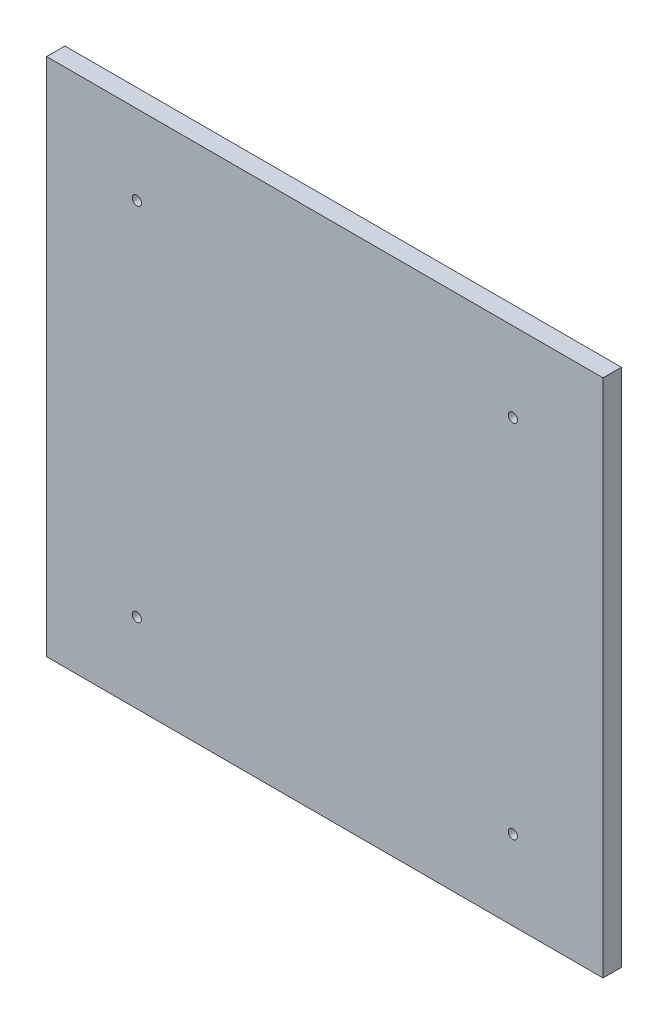
SolidWorks part; units mm, degrees
material "MDF"
ref_plane "Plano frontal" through (0, 0, 0) normal (0, 0, 1) x (1, 0, 0)
ref_plane "Plano superior" through (0, 0, 0) normal (0, 1, 0) x (1, 0, 0)
ref_plane "Plano direito" through (0, 0, 0) normal (1, 0, 0) x (0, 0, -1)
other "Centro da massa"
sketch "Esboço1" plane through (0, 0, 0) normal (0, 0, 1) x (1, 0, 0)
  line L0 (-61.5, 0) -> (61.5, 0) construction
  line L2 (91, -85) -> (-91, -85)
  line L3 (91, -85) -> (91, 85)
  line L4 (91, 85) -> (-91, 85)
  line L5 (-91, -85) -> (-91, 85)
  line L6 (91, -85) -> (-91, 85) construction
  line L7 (0, 67.0256) -> (0, -59) construction
  line L8 (91, 85) -> (-91, -85) construction
  circle A0 centre (-61.5, 59) radius 1.5
  circle A1 centre (61.5, 59) radius 1.5
  circle A2 centre (61.5, -59) radius 1.5
  circle A3 centre (-61.5, -59) radius 1.5
  point P0 (0, 0)
  point P1 (0, 0)
  point P19 (0, -85)
  point P20 (91, 0)
  dimension "D3" = 59
  dimension "D4" = 61.5
  dimension "D5" = 3
  dimension "D6" = 3
  dimension "D7" = 61.5
  dimension "D8" = 59
  dimension "D9" = 91
  dimension "D1" = 91
  dimension "D2" = 85
extrude "Ressalto-extrusão1" add sketch "Esboço1" along normal blind 6
sketch "Esboço2" plane through (0, 0, 6) normal (0, 0, 1) x (1, 0, 0)
  line L1 (78.5, -76) -> (-78.5, -76)
  line L2 (78.5, -76) -> (78.5, 76)
  line L3 (78.5, 76) -> (-78.5, 76)
  line L4 (-78.5, -76) -> (-78.5, 76)
  line L5 (15, -30) -> (-15, -30)
  line L6 (15, -30) -> (15, 30)
  line L7 (15, 30) -> (-15, 30)
  line L8 (-15, -30) -> (-15, 30)
  line L9 (15, -30) -> (-15, 30) construction
  line L10 (15, 30) -> (-15, -30) construction
  point P0 (0, 0)
  dimension "D1" = 60
  dimension "D2" = 30
